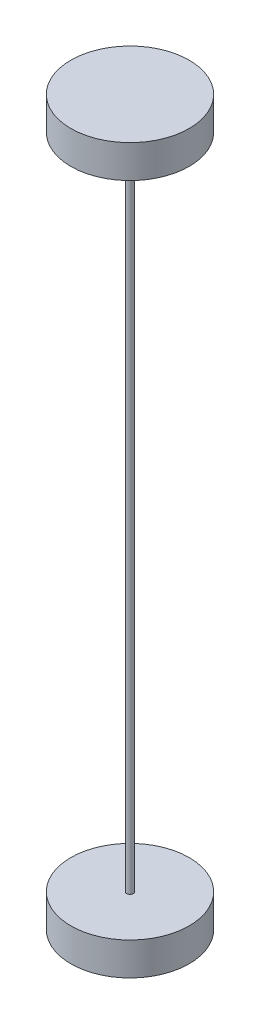
SolidWorks part; units mm, degrees
ref_plane "前视基准面" through (0, 0, 0) normal (0, 0, 1) x (1, 0, 0)
ref_plane "上视基准面" through (0, 0, 0) normal (0, 1, 0) x (1, 0, 0)
ref_plane "右视基准面" through (0, 0, 0) normal (1, 0, 0) x (0, 0, -1)
sketch "草图1" plane through (0, 0, 0) normal (0, 1, 0) x (1, 0, 0)
  circle A0 centre (0, 0) radius 18
extrude "凸台-拉伸1" add sketch "草图1" along normal blind 10 contours A0
sketch "草图2" plane through (0, 0, 0) normal (0, -1, 0) x (-1, 0, 0)
  circle A0 centre (0, 0) radius 1
extrude "凸台-拉伸2" add sketch "草图2" along normal blind 200
sketch "草图3" plane through (0, -200, 0) normal (0, -1, 0) x (-1, 0, 0)
  circle A0 centre (0, 0) radius 18
extrude "凸台-拉伸3" add sketch "草图3" along normal blind 10
